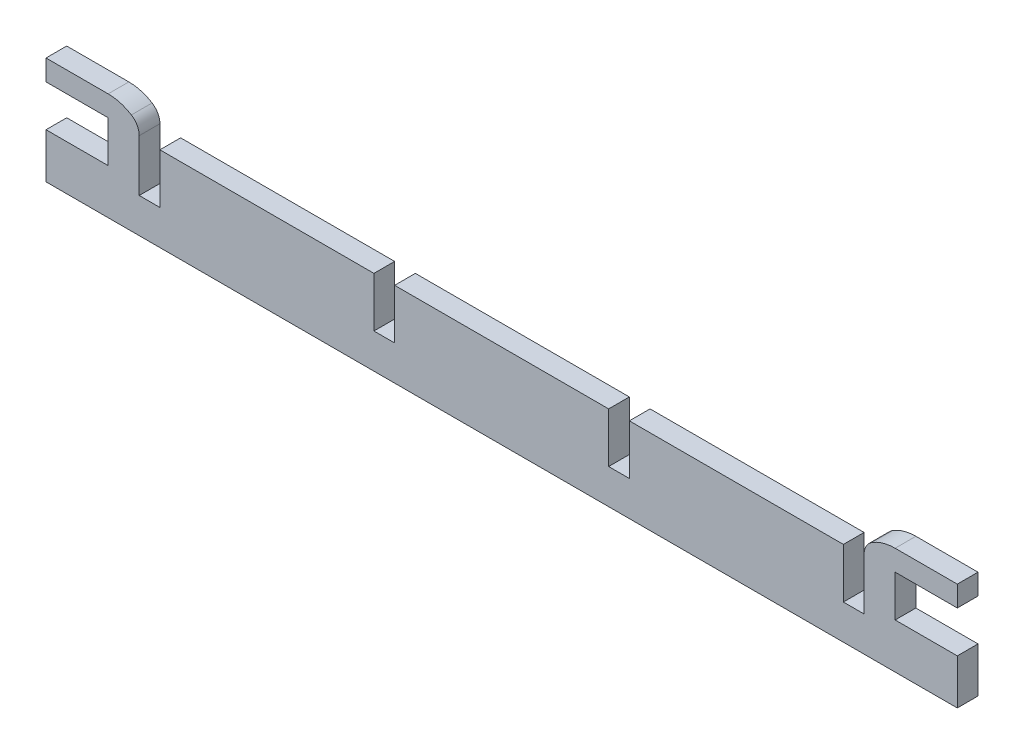
SolidWorks part; units mm, degrees
ref_plane "Front Plane" through (0, 0, 0) normal (0, 0, 1) x (1, 0, 0)
ref_plane "Top Plane" through (0, 0, 0) normal (0, 1, 0) x (1, 0, 0)
ref_plane "Right Plane" through (0, 0, 0) normal (1, 0, 0) x (0, 0, -1)
sketch "Sketch1" plane through (0, 0, 0) normal (0, 0, 1) x (1, 0, 0)
  line L0 (0, 0) -> (19.05, 0)
  line L1 (19.05, 0) -> (19.05, 12.7)
  line L2 (19.05, 12.7) -> (0, 12.7)
  line L3 (0, 12.7) -> (0, 19.05)
  line L4 (0, 19.05) -> (19.05, 19.05)
  line L6 (19.05, 0) -> (28.575, 0) construction
  line L7 (28.575, 0) -> (28.575, -3.175)
  line L8 (28.575, -3.175) -> (34.925, -3.175)
  line L9 (34.925, -3.175) -> (34.925, 12.1311)
  line L10 (34.925, 12.1311) -> (139.7, 12.1311)
  line L11 (0, 0) -> (0, -13.843)
  line L12 (0, -13.843) -> (139.7, -13.843)
  line L14 (28.575, 0) -> (28.575, 12.7)
  line L15 (28.575, 12.7) -> (19.05, 12.7) construction
  line L16 (19.05, 12.7) -> (19.05, 19.05) construction
  line L17 (25.4, 12.7) -> (58.9294, 12.7) construction
  line L18 (-23.1691, 12.1311) -> (-16.8191, 12.1311) construction
  line L19 (-28.575, 12.1311) -> (-22.225, 12.1311) construction
  line L25 (139.7, 12.1311) -> (139.7, -13.843)
  circle A4 centre (-25.4, 3.556) radius 9.144 construction
  arc A5 (19.05, 19.05) -> (26.1788, 17.0132) centre (19.05, 5.5562) cw
  arc A6 (26.1788, 17.0132) -> (28.575, 12.7) centre (23.495, 12.7) cw
  point P15 (26.7431, 10.344)
  point P22 (25.5682, 11.1821)
  dimension "D3" = 5.08
  dimension "D7" = 18.288
  dimension "D1" = 6.35
  dimension "D4" = 19.05
  dimension "D5" = 34.925
  dimension "D6" = 10.668
  dimension "D8" = 25.4
  dimension "D9" = 6.35
  dimension "D10" = 139.7
  dimension "D11" = 12.7
  dimension "D12" = 26.543
extrude "Boss-Extrude1" add sketch "Sketch1" along normal blind 6.35
mirror "Mirror1" about plane through (139.7, 12.1311, 6.35) normal (-1, 0, 0) of "Boss-Extrude1"
sketch "Sketch2" plane through (0, 0, 6.35) normal (0, 0, 1) x (1, 0, 0)
  line L0 (103.7167, -3.175) -> (175.6833, -3.175) construction
  line L3 (31.75, -3.175) -> (103.7167, -3.175) construction
  line L4 (34.925, -3.175) -> (28.575, -3.175) construction
  line L5 (175.6833, -3.175) -> (247.65, -3.175) construction
  line L6 (244.475, -3.175) -> (250.825, -3.175) construction
  line L7 (103.7167, -3.175) -> (103.7167, 12.1311) construction
  line L8 (244.475, 12.1311) -> (34.925, 12.1311) construction
  line L9 (175.6833, -3.175) -> (175.6833, 12.1311) construction
  line L11 (106.8917, -3.175) -> (100.5417, -3.175)
  line L12 (106.8917, -3.175) -> (106.8917, 12.1311)
  line L13 (106.8917, 12.1311) -> (100.5417, 12.1311)
  line L14 (100.5417, -3.175) -> (100.5417, 12.1311)
  line L15 (106.8917, -3.175) -> (100.5417, 12.1311) construction
  line L16 (106.8917, 12.1311) -> (100.5417, -3.175) construction
  line L17 (178.8583, -3.175) -> (172.5083, -3.175)
  line L18 (178.8583, -3.175) -> (178.8583, 12.1311)
  line L19 (178.8583, 12.1311) -> (172.5083, 12.1311)
  line L20 (172.5083, -3.175) -> (172.5083, 12.1311)
  line L21 (178.8583, -3.175) -> (172.5083, 12.1311) construction
  line L22 (178.8583, 12.1311) -> (172.5083, -3.175) construction
  point P13 (103.7167, 4.478)
  point P18 (175.6833, 4.478)
extrude "Cut-Extrude1" cut sketch "Sketch2" against normal through all
